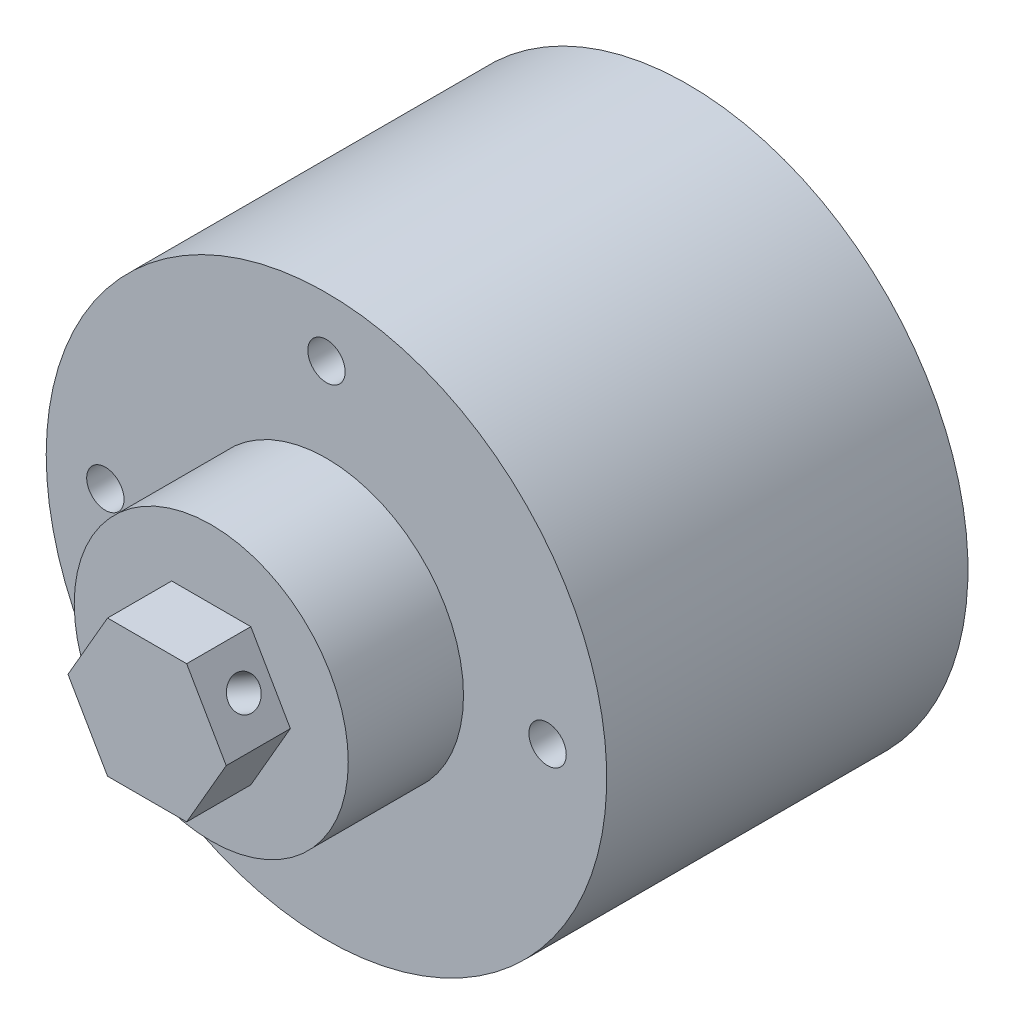
SolidWorks part; units mm, degrees
ref_plane "Alzado" through (0, 0, 0) normal (0, 0, 1) x (1, 0, 0)
ref_plane "Planta" through (0, 0, 0) normal (0, 1, 0) x (1, 0, 0)
ref_plane "Vista lateral" through (0, 0, 0) normal (1, 0, 0) x (0, 0, -1)
sketch "Croquis1" plane through (0, 0, 0) normal (0, 0, 1) x (1, 0, 0)
  circle A0 centre (0, 0) radius 45
  dimension "D1" = 90
extrude "Saliente-Extruir1" add sketch "Croquis1" along normal blind 58
sketch "Croquis2" plane through (0, 0, 58) normal (0, 0, 1) x (1, 0, 0)
  circle A0 centre (0, 0) radius 22
  dimension "D1" = 44
extrude "Saliente-Extruir2" add sketch "Croquis2" along normal blind 18.5
sketch "Croquis3" plane through (0, 0, 76.5) normal (0, 0, 1) x (1, 0, 0)
  line L1 (12.7017, 0) -> (6.3509, 11)
  line L2 (6.3509, 11) -> (-6.3509, 11)
  line L3 (-6.3509, 11) -> (-12.7017, 0)
  line L4 (-12.7017, 0) -> (-6.3509, -11)
  line L5 (-6.3509, -11) -> (6.3509, -11)
  line L6 (6.3509, -11) -> (12.7017, 0)
  circle A0 centre (0, 0) radius 11 construction
  dimension "D1" = 22
extrude "Saliente-Extruir3" add sketch "Croquis3" along normal blind 10.3
sketch "Croquis4" plane through (9.5263, 5.5, 0) normal (0.866, 0.5, 0) x (0, 0, -1)
  line L1 (-86.8, 6.3509) -> (-86.8, 12.7017) construction
  circle A0 centre (-80.8, 0) radius 2.5
  dimension "D1" = 5
  dimension "D2" = 6
extrude "Cortar-Extruir1" cut sketch "Croquis4" against normal through all
sketch "Croquis5" plane through (0, 0, 58) normal (0, 0, 1) x (1, 0, 0)
  circle A0 centre (0, 0) radius 35.5 construction
  circle A1 centre (-35.5, 0) radius 3
  circle A2 centre (35.5, 0) radius 3
  circle A3 centre (0, 35.5) radius 3
  dimension "D1" = 71
  dimension "D2" = 6
  dimension "D3" = 6
  dimension "D4" = 6
extrude "Cortar-Extruir2" cut sketch "Croquis5" against normal blind 10
